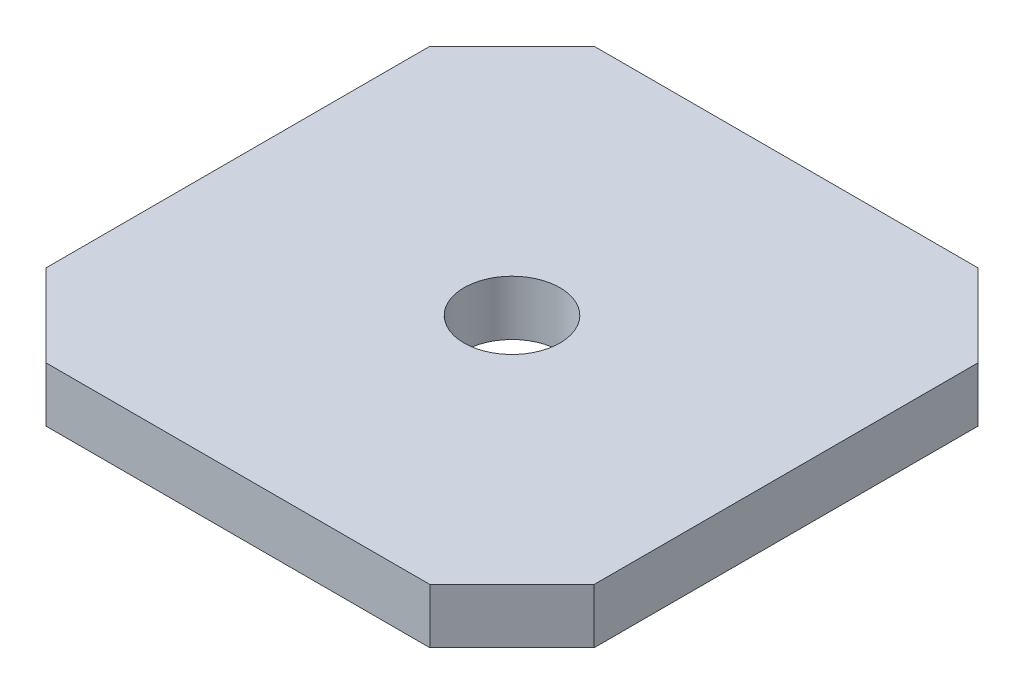
SolidWorks part; units mm, degrees
material "Aluminium"
ref_plane "Front Plane" through (0, 0, 0) normal (0, 0, 1) x (1, 0, 0)
ref_plane "Top Plane" through (0, 0, 0) normal (0, 1, 0) x (1, 0, 0)
ref_plane "Right Plane" through (0, 0, 0) normal (1, 0, 0) x (0, 0, -1)
sketch "Sketch1" plane through (0, 0, 0) normal (0, 1, 0) x (1, 0, 0)
  line L0 (-10, 10) -> (10, -10) construction
  line L1 (-10, 10) -> (10, 10)
  line L2 (-10, 10) -> (-10, -10)
  line L3 (-10, -10) -> (10, -10)
  line L4 (10, 10) -> (10, -10)
  circle A0 centre (0, 0) radius 1.75
  dimension "D1" = 3.5
  dimension "D2" = 20
extrude "Boss-Extrude1" add sketch "Sketch1" along normal blind 2
chamfer "Chamfer1" distance 3 angle 45 4 edges at (-10, 1, -10) (10, 1, -10) (10, 1, 10) (-10, 1, 10)
